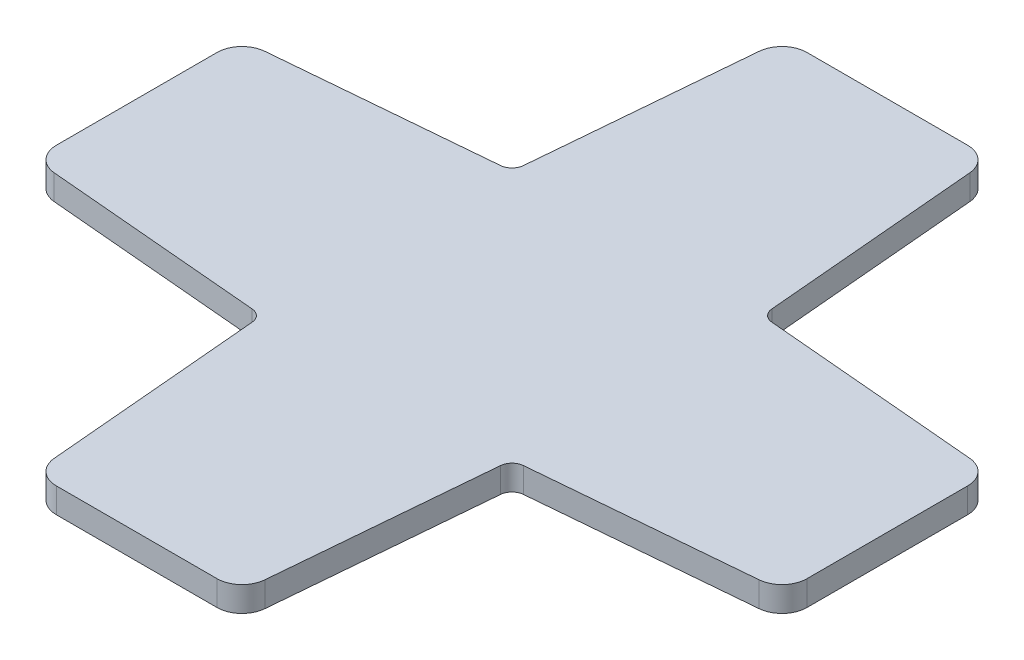
SolidWorks part; units mm, degrees
ref_plane "Front Plane" through (0, 0, 0) normal (0, 0, 1) x (1, 0, 0)
ref_plane "Top Plane" through (0, 0, 0) normal (0, 1, 0) x (1, 0, 0)
ref_plane "Right Plane" through (0, 0, 0) normal (1, 0, 0) x (0, 0, -1)
sketch "Sketch1" plane through (0, 0, 0) normal (0, 1, 0) x (1, 0, 0)
  line L0 (0, 0) -> (0, 45) construction
  line L1 (0, 0) -> (0, -45) construction
  line L2 (-45, 0) -> (45, 0) construction
  line L3 (45, -45) -> (-45, -45) construction
  line L4 (45, -45) -> (45, 45) construction
  line L5 (45, 45) -> (-45, 45) construction
  line L6 (-45, -45) -> (-45, 45) construction
  line L7 (45, -45) -> (-45, 45) construction
  line L8 (45, 45) -> (-45, -45) construction
  line L9 (-14.715, 18.261) -> (-12.62, 42.261) construction
  line L10 (-45, 15) -> (45, 15) construction
  line L11 (-14.8902, 16.2541) -> (-12.62, 42.2609)
  line L12 (14.715, 18.261) -> (12.62, 42.261) construction
  line L13 (14.8902, 16.2541) -> (12.62, 42.2609)
  line L14 (14.715, -18.261) -> (12.62, -42.261) construction
  line L15 (-14.715, -18.261) -> (-12.62, -42.261) construction
  line L16 (9.6314, -45) -> (-9.6314, -45)
  line L17 (14.8902, -16.2541) -> (12.62, -42.2609)
  line L18 (-14.8902, -16.2541) -> (-12.62, -42.2609)
  line L19 (18.261, -14.715) -> (42.261, -12.62) construction
  line L20 (16.2541, -14.8902) -> (42.2609, -12.62)
  line L21 (-18.261, 14.715) -> (-42.261, 12.62) construction
  line L22 (9.6314, 45) -> (-9.6314, 45)
  line L23 (-16.2541, 14.8902) -> (-42.2609, 12.62)
  line L24 (-18.261, -14.715) -> (-42.261, -12.62) construction
  line L25 (-16.2541, -14.8902) -> (-42.2609, -12.62)
  line L26 (18.261, 14.715) -> (42.261, 12.62) construction
  line L27 (16.2541, 14.8902) -> (42.2609, 12.62)
  line L28 (-45, 9.6314) -> (-45, -9.6314)
  line L29 (45, 9.6314) -> (45, -9.6314)
  arc A0 (12.62, 42.2609) -> (9.6314, 45) centre (9.6314, 42) ccw
  arc A1 (-12.62, -42.2609) -> (-9.6314, -45) centre (-9.6314, -42) ccw
  arc A2 (12.62, -42.2609) -> (9.6314, -45) centre (9.6314, -42) cw
  arc A3 (42.2609, -12.62) -> (45, -9.6314) centre (42, -9.6314) ccw
  arc A4 (-42.2609, 12.62) -> (-45, 9.6314) centre (-42, 9.6314) ccw
  arc A5 (-42.2609, -12.62) -> (-45, -9.6314) centre (-42, -9.6314) cw
  arc A6 (42.2609, 12.62) -> (45, 9.6314) centre (42, 9.6314) cw
  arc A7 (-12.62, 42.2609) -> (-9.6314, 45) centre (-9.6314, 42) cw
  arc A8 (14.8902, 16.2541) -> (16.2541, 14.8902) centre (16.3845, 16.3845) ccw
  arc A9 (16.2541, -14.8902) -> (14.8902, -16.2541) centre (16.3845, -16.3845) ccw
  arc A10 (-14.8902, -16.2541) -> (-16.2541, -14.8902) centre (-16.3845, -16.3845) ccw
  arc A11 (-16.2541, 14.8902) -> (-14.8902, 16.2541) centre (-16.3845, 16.3845) ccw
  point P22 (12.3809, 45)
  point P35 (-12.3809, -45)
  point P36 (12.3809, -45)
  point P42 (45, -12.3809)
  point P48 (-45, 12.3809)
  point P53 (-12.3809, 45)
  point P57 (-45, -12.3809)
  point P63 (45, 12.3809)
  point P66 (14.9997, 14.9997)
  point P69 (14.9997, -14.9997)
  point P72 (-14.9997, -14.9997)
  point P75 (-14.9997, 14.9997)
  dimension "D8" = 3
  dimension "D9" = 1.5
  dimension "D1" = 90
  dimension "D2" = 90
  dimension "D3" = 14.715
  dimension "D4" = 12.62
  dimension "D5" = 30
  dimension "D6" = 2.739
  dimension "D7" = 3.261
extrude "Boss-Extrude1" add sketch "Sketch1" along normal blind 3
